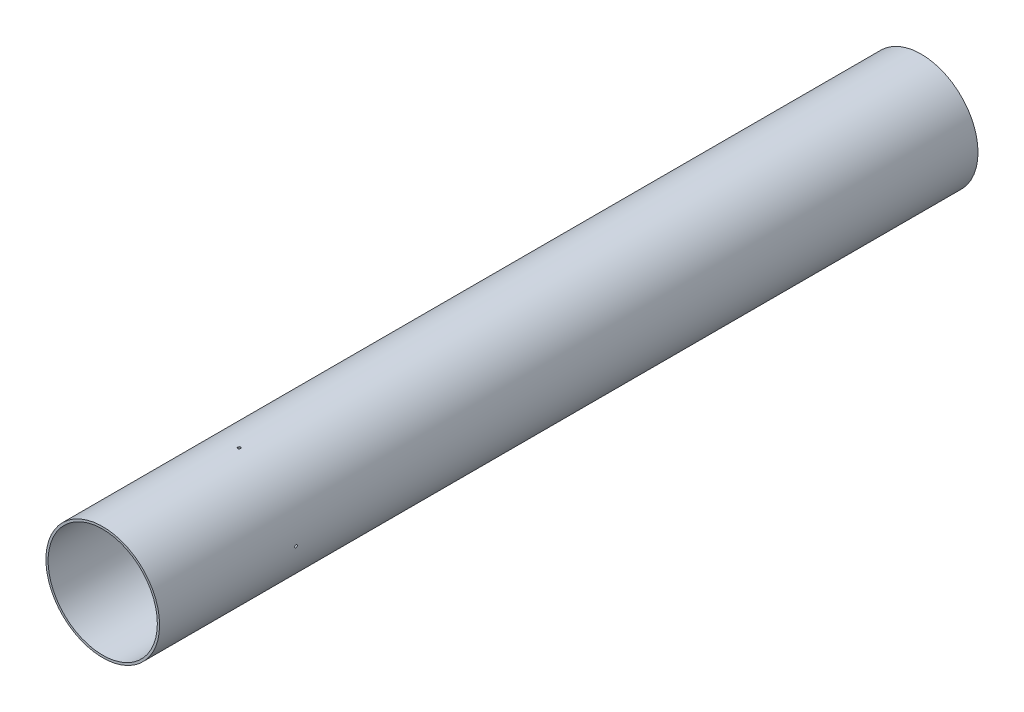
SolidWorks part; units mm, degrees
material "6061-T6 (SS)"
ref_plane "Front Plane" through (0, 0, 0) normal (0, 0, 1) x (1, 0, 0)
ref_plane "Top Plane" through (0, 0, 0) normal (0, 1, 0) x (1, 0, 0)
ref_plane "Right Plane" through (0, 0, 0) normal (1, 0, 0) x (0, 0, -1)
sketch "Sketch1" plane through (0, 0, 0) normal (0, 0, 1) x (1, 0, 0)
  circle A0 centre (0, 0) radius 30.5054
  circle A1 centre (0, 0) radius 31.75
  dimension "D1" = 63.5
  dimension "D2" = 1.2446
extrude "Boss-Extrude1" add sketch "Sketch1" along normal blind 457.2
sketch "Sketch2" [suppressed] plane through (0, 0, 0) normal (1, 0, 0) x (0, 0, -1)
  line L0 (-355.6, 38.1) -> (-355.6, -38.1) construction
  line L1 (-336.55, 12.7) -> (-285.75, 12.7)
  line L2 (-336.55, 12.7) -> (-336.55, -12.7)
  line L3 (-336.55, -12.7) -> (-285.75, -12.7)
  line L4 (-285.75, 12.7) -> (-285.75, -12.7)
  line L5 (-336.55, 12.7) -> (-285.75, -12.7) construction
  line L6 (-336.55, -12.7) -> (-285.75, 12.7) construction
  point P0 (-311.15, 0)
  dimension "D1" = 25.4
  dimension "D2" = 50.8
  dimension "D3" = 19.05
sketch "Sketch3" plane through (0, 0, 0) normal (0, 1, 0) x (1, 0, 0)
  circle A0 centre (0, -381) radius 0.75
  dimension "D1" = 1.5
  dimension "D2" = 381
extrude "Cut-Extrude1" cut sketch "Sketch3" against normal through all and the other way through all
pattern_circular "CirPattern1" count 4 over 360 about axis through (0, 0, 457.2) along (0, 0, -1) of "Cut-Extrude1"
